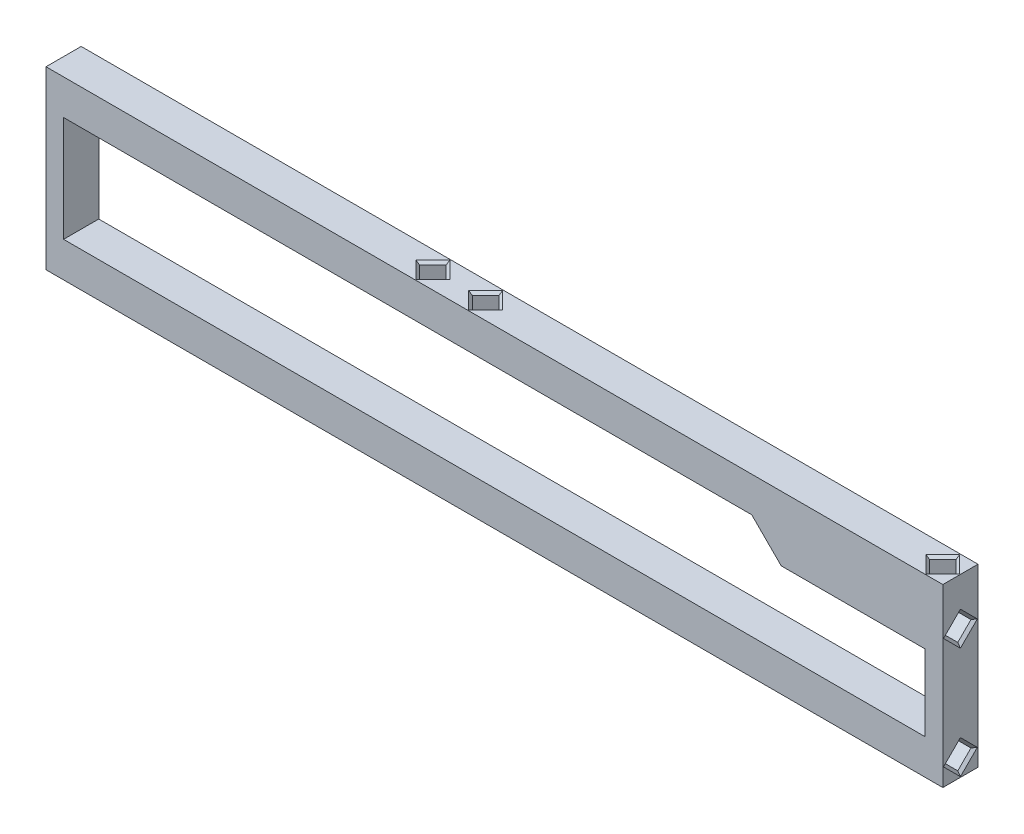
SolidWorks part; units mm, degrees
ref_plane "Front Plane" through (0, 0, 0) normal (0, 0, 1) x (1, 0, 0)
ref_plane "Top Plane" through (0, 0, 0) normal (0, 1, 0) x (1, 0, 0)
ref_plane "Right Plane" through (0, 0, 0) normal (1, 0, 0) x (0, 0, -1)
sketch "Sketch1" plane through (0, 0, 0) normal (0, 0, 1) x (1, 0, 0)
  line L0 (-107.95, 21.1667) -> (107.95, 21.1667)
  line L1 (-103.7167, -12.7) -> (103.7167, -12.7)
  line L2 (-107.95, 21.1667) -> (-107.95, -21.1667)
  line L3 (-107.95, -21.1667) -> (107.95, -21.1667)
  line L4 (107.95, 21.1667) -> (107.95, -21.1667)
  line L5 (-103.7167, -12.7) -> (-103.7167, 12.7)
  line L6 (-103.7167, 12.7) -> (61.9506, 12.7)
  line L7 (103.7167, 5.6049) -> (103.7167, -12.7)
  line L8 (61.9506, 12.7) -> (69.0457, 5.6049)
  line L9 (69.0457, 5.6049) -> (103.7167, 5.6049)
  point P3 (-103.7167, 0)
  point P4 (0, -12.7)
  point P16 (0, 21.1667)
  dimension "D1" = 8.4667
  dimension "D2" = 215.9
  dimension "D3" = 8.4667
  dimension "D4" = 42.3333
  dimension "D5" = 4.2333
  dimension "D6" = 18.3049
  dimension "D7" = 165.6673
  dimension "D8" = 45
extrude "Boss-Extrude1" add sketch "Sketch1" along normal blind 8.4667
sketch "Sketch3" plane through (-107.95, 0, 91.2066) normal (1, 0, 0) x (0, 0, -1)
  line L0 (83.7983, 16.9333) -> (86.9733, 20.1083)
  line L1 (83.7983, 16.9333) -> (86.9733, 13.7583)
  line L2 (86.9733, 20.1083) -> (90.1483, 16.9333)
  line L3 (86.9733, 13.7583) -> (90.1483, 16.9333)
  line L4 (83.7983, 16.9333) -> (90.1483, 16.9333) construction
  line L5 (86.9733, 20.1083) -> (86.9733, 13.7583) construction
  line L6 (82.74, -21.1667) -> (82.74, 21.1667) construction
  line L7 (82.74, 21.1667) -> (91.2066, 21.1667) construction
  line L8 (86.9733, -20.1083) -> (83.7983, -16.9333)
  line L9 (86.9733, -20.1083) -> (90.1483, -16.9333)
  line L10 (83.7983, -16.9333) -> (86.9733, -13.7583)
  line L11 (90.1483, -16.9333) -> (86.9733, -13.7583)
  line L12 (86.9733, -20.1083) -> (86.9733, -13.7583) construction
  line L13 (83.7983, -16.9333) -> (90.1483, -16.9333) construction
  line L14 (82.74, -21.1667) -> (91.2066, -21.1667) construction
  point P0 (86.9733, 16.9333)
  point P11 (86.9733, -16.9333)
  dimension "D1" = 6.35
  dimension "D2" = 4.2333
  dimension "D3" = 4.2333
  dimension "D4" = 4.2333
extrude "rear pin" cut sketch "Sketch3" along normal blind 6.35
sketch "Sketch4" plane through (107.95, 0, 0) normal (1, 0, 0) x (0, 0, -1)
  line L0 (-1.0583, 9.8383) -> (-4.2333, 13.0133)
  line L1 (-1.0583, 9.8383) -> (-4.2333, 6.6633)
  line L2 (-4.2333, 13.0133) -> (-7.4083, 9.8383)
  line L3 (-4.2333, 6.6633) -> (-7.4083, 9.8383)
  line L4 (-1.0583, 9.8383) -> (-7.4083, 9.8383) construction
  line L5 (-4.2333, 13.0133) -> (-4.2333, 6.6633) construction
  line L6 (-1.0583, -16.9333) -> (-4.2333, -13.7583)
  line L7 (-1.0583, -16.9333) -> (-4.2333, -20.1083)
  line L8 (-4.2333, -13.7583) -> (-7.4083, -16.9333)
  line L9 (-4.2333, -20.1083) -> (-7.4083, -16.9333)
  line L10 (-1.0583, -16.9333) -> (-7.4083, -16.9333) construction
  line L11 (-4.2333, -13.7583) -> (-4.2333, -20.1083) construction
  line L12 (-8.4667, 21.1667) -> (0, 21.1667) construction
  line L13 (-8.4667, -21.1667) -> (0, -21.1667) construction
  line L14 (-8.4667, 5.6049) -> (0, 5.6049) construction
  point P1 (-4.2333, 9.8383)
  point P2 (-4.2333, -16.9333)
  point P13 (-4.2333, 21.1667)
  dimension "D1" = 6.35
  dimension "D2" = 4.2333
  dimension "D3" = 4.2333
extrude "front pin" cut sketch "Sketch4" against normal blind 6.35
sketch "Sketch5" plane through (0, 21.1667, 0) normal (0, 1, 0) x (1, 0, 0)
  line L0 (106.8917, -4.2333) -> (103.7167, -7.4083)
  line L1 (106.8917, -4.2333) -> (103.7167, -1.0583)
  line L2 (103.7167, -7.4083) -> (100.5417, -4.2333)
  line L3 (103.7167, -1.0583) -> (100.5417, -4.2333)
  line L4 (106.8917, -4.2333) -> (100.5417, -4.2333) construction
  line L5 (103.7167, -7.4083) -> (103.7167, -1.0583) construction
  line L6 (107.95, -8.4667) -> (107.95, 0) construction
  line L7 (-3.175, -4.2333) -> (-6.35, -7.4083)
  line L8 (-3.175, -4.2333) -> (-6.35, -1.0583)
  line L9 (-6.35, -7.4083) -> (-9.525, -4.2333)
  line L10 (-6.35, -1.0583) -> (-9.525, -4.2333)
  line L11 (-3.175, -4.2333) -> (-9.525, -4.2333) construction
  line L12 (-6.35, -7.4083) -> (-6.35, -1.0583) construction
  line L13 (-15.875, -4.2333) -> (-19.05, -7.4083)
  line L15 (-15.875, -4.2333) -> (-19.05, -1.0583)
  line L16 (-19.05, -7.4083) -> (-22.225, -4.2333)
  line L17 (-19.05, -1.0583) -> (-22.225, -4.2333)
  line L18 (-15.875, -4.2333) -> (-22.225, -4.2333) construction
  line L19 (-19.05, -7.4083) -> (-19.05, -1.0583) construction
  point P1 (103.7167, -4.2333)
  point P8 (107.95, -4.2333)
  point P9 (-6.35, -4.2333)
  point P10 (-19.05, -4.2333)
  dimension "D1" = 4.2333
  dimension "D2" = 6.35
  dimension "D3" = 110.0667
  dimension "D4" = 12.7
extrude "top pins" cut sketch "Sketch5" against normal blind 6.35
chamfer "pin chamfer" distance 0.635 angle 45 56 edges at (-101.6, 15.3458, 2.6458) (-101.6, 18.5208, 2.6458) (-101.6, 18.5208, 5.8208) (-101.6, 15.3458, 5.8208) (101.6, -18.5208, 5.8208) (101.6, -15.3458, 5.8208) (101.6, -15.3458, 2.6458) (101.6, -18.5208, 2.6458) (101.6, 8.2508, 5.8208) (101.6, 11.4258, 5.8208) (101.6, 11.4258, 2.6458) (101.6, 8.2508, 2.6458) (-107.95, 18.5208, 5.8208) (-107.95, 15.3458, 5.8208) (-107.95, 15.3458, 2.6458) (-107.95, 18.5208, 2.6458) (-101.6, -15.3458, 2.6458) (-101.6, -18.5208, 2.6458) (-101.6, -18.5208, 5.8208) (-101.6, -15.3458, 5.8208) (-107.95, -18.5208, 5.8208) (-107.95, -18.5208, 2.6458) (-107.95, -15.3458, 2.6458) (107.95, -18.5208, 5.8208) (107.95, -18.5208, 2.6458) (107.95, -15.3458, 2.6458) (107.95, -15.3458, 5.8208) (107.95, 8.2508, 5.8208) (107.95, 8.2508, 2.6458) (107.95, 11.4258, 2.6458) (107.95, 11.4258, 5.8208) (-107.95, -15.3458, 5.8208) (-4.7625, 14.8167, 5.8208) (-7.9375, 14.8167, 5.8208) (-7.9375, 14.8167, 2.6458) (-4.7625, 14.8167, 2.6458) (-17.4625, 14.8167, 5.8208) (-20.6375, 14.8167, 5.8208) (-20.6375, 14.8167, 2.6458) (-17.4625, 14.8167, 2.6458) (105.3042, 14.8167, 5.8208) (102.1292, 14.8167, 5.8208) (102.1292, 14.8167, 2.6458) (105.3042, 14.8167, 2.6458) (-17.4625, 21.1667, 2.6458) (-20.6375, 21.1667, 2.6458) (-20.6375, 21.1667, 5.8208) (-17.4625, 21.1667, 5.8208) (-7.9375, 21.1667, 2.6458) (-4.7625, 21.1667, 2.6458) (-4.7625, 21.1667, 5.8208) (-7.9375, 21.1667, 5.8208) (105.3042, 21.1667, 2.6458) (102.1292, 21.1667, 2.6458) (102.1292, 21.1667, 5.8208) (105.3042, 21.1667, 5.8208)
